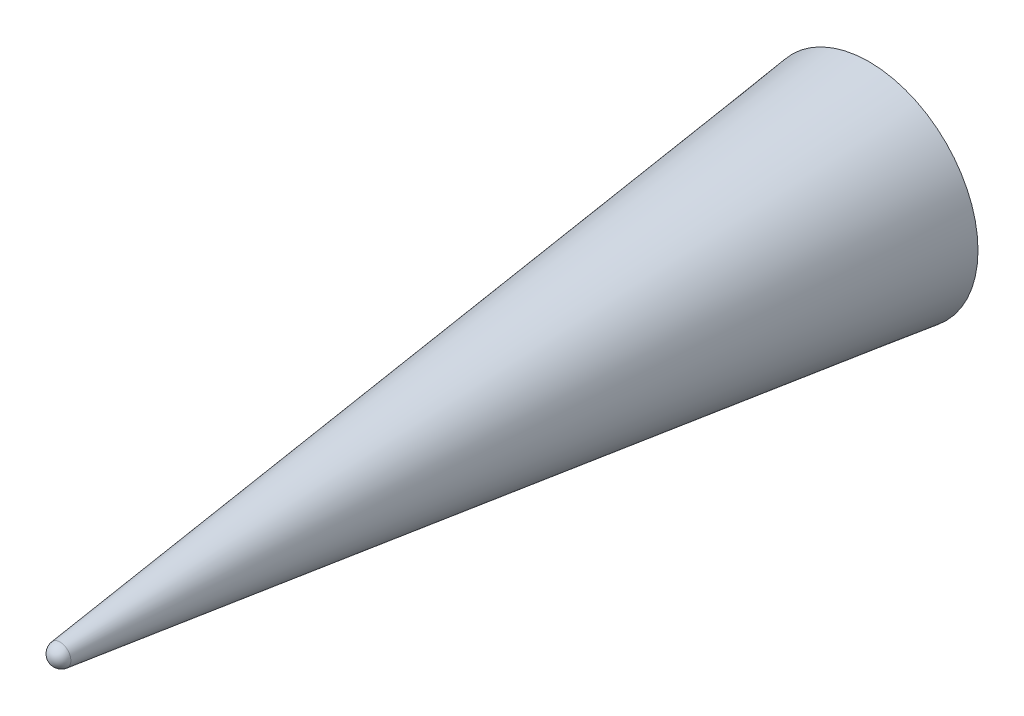
SolidWorks part; units mm, degrees
ref_plane "Front Plane" through (0, 0, 0) normal (0, 0, 1) x (1, 0, 0)
ref_plane "Top Plane" through (0, 0, 0) normal (0, 1, 0) x (1, 0, 0)
ref_plane "Right Plane" through (0, 0, 0) normal (1, 0, 0) x (0, 0, -1)
sketch "Sketch1" plane through (0, 0, 0) normal (1, 0, 0) x (0, 0, -1)
  line L0 (-477.5718, 0) -> (-357.9276, 0) construction
  line L3 (-381.9632, 0) -> (0, 0)
  line L4 (0, 50.8) -> (0, 0)
  line L5 (0, 50.8) -> (-377.4945, 5.0431)
  arc A0 (-377.4945, 5.0431) -> (-381.9632, 0) centre (-376.8832, 0) ccw
  arc A1 (-371.8032, 0) -> (-377.4945, 5.0431) centre (-376.8832, 0) ccw construction
  spline S0 degree 1 poles (-461.01, -5.08) (41.4909, 55.8292) knots 0 0 1 1 construction
  spline S1 degree 1 poles (-419.1, 0) (0, 50.8) knots 0.083403 0.083403 0.917431 0.917431 construction
  point P9 (-398.2973, 12.6077)
  dimension "D4" = 5.08
  dimension "D1" = 50.8
  dimension "D2" = 398.2973
  dimension "D3" = 12.6077
revolve "Revolve1" add sketch "Sketch1" angle 360 about L0
equation "\"R\"= 2'base radius"
equation "\"L\"= 16.5'overall length"
equation "\"phi\"= atn ( \"R\" / \"L\" )'half angle"
equation "\"rn\"= .1'blunted nose radius"
equation "\"xt\"= ( \"L\" ^ 2 / \"R\" ) * sqr ( \"rn\" ^ 2 / ( \"R\" ^ 2 + \"L\" ^ 2 ) )'tangency x-coordinate"
equation "\"yt\"= \"xt\" * \"R\" / \"L\"'tangency y-coordinate"
equation "\"xo\"= \"xt\" + sqr ( \"rn\" ^ 2 - \"yt\" ^ 2 )'center of spherical nose cap"
equation "\"xa\"= \"xo\" - \"rn\"'apex point"
equation "\"D4@Sketch1\"=\"rn\"*2"
equation "\"D2@Sketch1\"=\"L\" - ((\"L\"^2 / \"R\") * sqr(\"rn\"^2 / (\"R\"^2 + \"L\"^2)))"
